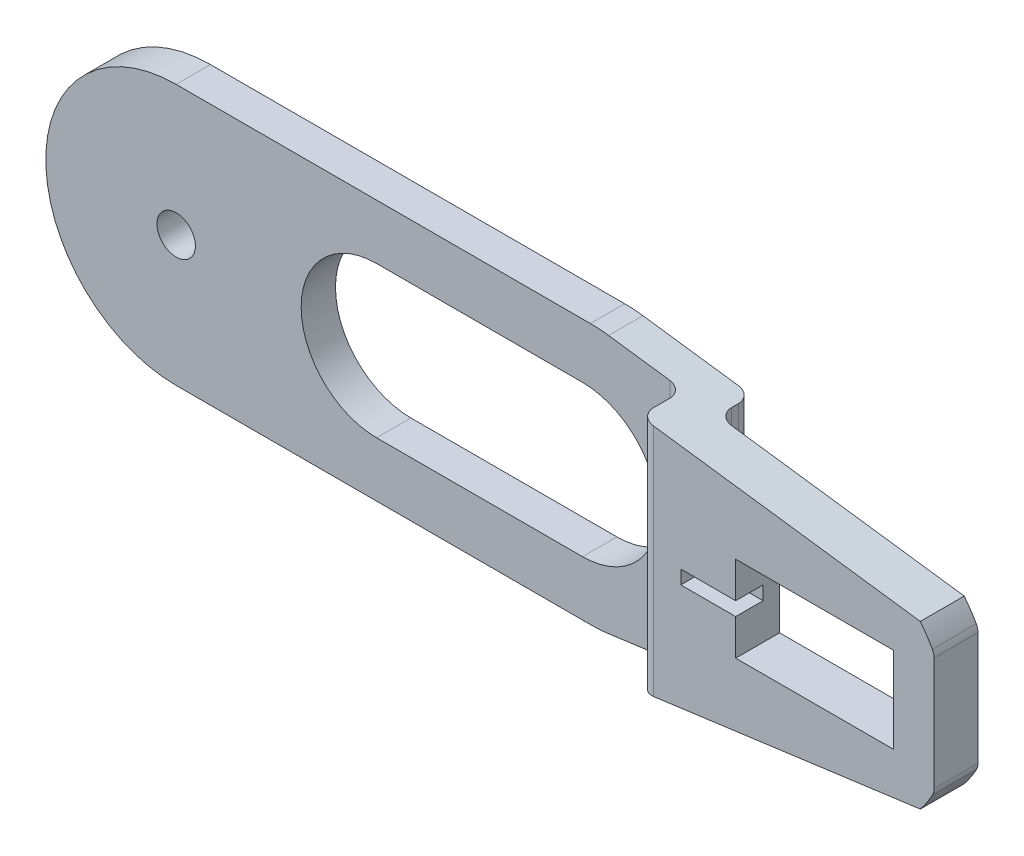
SolidWorks part; units mm, degrees
ref_plane "Front Plane" through (0, 0, 0) normal (0, 0, 1) x (1, 0, 0)
ref_plane "Top Plane" through (0, 0, 0) normal (0, 1, 0) x (1, 0, 0)
ref_plane "Right Plane" through (0, 0, 0) normal (1, 0, 0) x (0, 0, -1)
sketch "Sketch1" plane through (0, 0, 0) normal (0, 0, 1) x (1, 0, 0)
  line L0 (0, 0) -> (100, 0) construction
  line L1 (0, 19) -> (100, 19)
  line L2 (0, -19) -> (100, -19)
  line L3 (29.2177, 0) -> (59.2177, 0) construction
  line L4 (29.2177, 11) -> (59.2177, 11)
  line L5 (29.2177, -11) -> (59.2177, -11)
  line L7 (87.9426, -6.25) -> (117.9426, -6.25)
  line L8 (87.9426, -6.25) -> (87.9426, 6.25)
  line L9 (87.9426, 6.25) -> (117.9426, 6.25)
  line L11 (87.9426, -6.25) -> (125.1488, 13.036) construction
  line L12 (87.9426, 6.25) -> (124.7544, -12.8315) construction
  circle A0 centre (0, 0) radius 2.8
  arc A1 (0, 19) -> (0, -19) centre (0, 0) ccw
  arc A2 (100, -19) -> (117.9426, -6.25) centre (100, 0) ccw
  arc A3 (29.2177, 11) -> (29.2177, -11) centre (29.2177, 0) ccw
  arc A4 (59.2177, -11) -> (59.2177, 11) centre (59.2177, 0) ccw
  arc A5 (117.9426, 6.25) -> (100, 19) centre (100, 0) ccw
  point P8 (44.2177, 0)
  point P17 (100, 0)
  dimension "D1" = 38
  dimension "D2" = 5.6
  dimension "D4" = 38
  dimension "D3" = 100
  dimension "D5" = 30
  dimension "D6" = 8
  dimension "D7" = 12.5
  dimension "D8" = 30
extrude "Boss-Extrude1" add sketch "Sketch1" along normal blind 5
fillet "Fillet1" radius 2 2 edges at (117.9426, 6.25, 2.5) (117.9426, -6.25, 2.5)
sketch "Sketch2" plane through (0, 0, 5) normal (0, 0, 1) x (1, 0, 0)
  line L0 (73.9426, 19) -> (73.9426, -19)
  line L1 (100, 19) -> (0, 19) construction
  line L2 (0, -19) -> (100, -19) construction
  line L3 (87.9426, -6.25) -> (87.9426, 6.25) construction
  line L4 (100, 19) -> (73.9426, 19)
  line L6 (73.9426, -19) -> (100, -19)
  line L7 (114.864, -6.25) -> (87.9426, -6.25) construction
  line L8 (114.864, -6.25) -> (87.9426, -6.25)
  line L9 (87.9426, -6.25) -> (87.9426, 6.25)
  line L10 (87.9426, 6.25) -> (114.864, 6.25) construction
  line L11 (87.9426, 6.25) -> (114.864, 6.25)
  arc A0 (116.6127, 9.2206) -> (100, 19) centre (100, 0) ccw construction
  arc A1 (116.6127, 9.2206) -> (100, 19) centre (100, 0) ccw
  arc A2 (100, -19) -> (116.6127, -9.2206) centre (100, 0) ccw construction
  arc A3 (100, -19) -> (116.6127, -9.2206) centre (100, 0) ccw
  arc A4 (116.6127, -9.2206) -> (114.864, -6.25) centre (114.864, -8.25) ccw construction
  arc A5 (116.6127, -9.2206) -> (114.864, -6.25) centre (114.864, -8.25) ccw
  arc A6 (114.864, 6.25) -> (116.6127, 9.2206) centre (114.864, 8.25) ccw construction
  arc A7 (114.864, 6.25) -> (116.6127, 9.2206) centre (114.864, 8.25) ccw
  point P8 (87.9426, 0)
  dimension "D1" = 14
extrude "Boss-Extrude2" add sketch "Sketch2" along normal blind 6.4
fillet "Fillet2" radius 2 2 edges at (73.9426, 0, 11.4) (73.9426, 0, 5)
sketch "Sketch3" plane through (0, 0, 11.4) normal (0, 0, 1) x (1, 0, 0)
  line L0 (87.9426, 0) -> (75.9426, 0) construction
  line L1 (87.9426, -6.25) -> (87.9426, 6.25) construction
  line L2 (75.9426, 19) -> (75.9426, -19) construction
  line L3 (87.9426, 1) -> (79.9426, 1)
  line L4 (87.9426, -1) -> (79.9426, -1)
  line L5 (87.9426, 1) -> (87.9426, -1)
  line L6 (79.9426, 1) -> (79.9426, -1)
  line L8 (87.9426, 1) -> (75.9426, 1) construction
  line L9 (87.9426, -1) -> (75.9426, -1) construction
  dimension "D3" = 4
  dimension "D1" = 1
  dimension "D2" = 1
extrude "Cut-Extrude1" cut sketch "Sketch3" against normal blind 4
sketch "Sketch5" plane through (0, 0, 5) normal (0, 0, 1) x (1, 0, 0)
  line L0 (71.9426, 19) -> (0, 19) construction
  line L1 (71.9426, -19) -> (71.9426, 19) construction
  circle A0 centre (66.9426, 10) radius 2
  circle A1 centre (80.9146, -4.3103) radius 2
  dimension "D1" = 20
  dimension "D3" = 4
  dimension "D2" = 9
  dimension "D4" = 5
sketch "Sketch6" plane through (0, 0, 0) normal (0, 0, -1) x (-1, 0, 0)
  line L0 (-78.9426, -19) -> (-78.9426, 19)
  line L1 (0, -19) -> (-100, -19) construction
  line L2 (-100, 19) -> (0, 19) construction
  line L3 (-78.9426, -19) -> (-183.2299, -19)
  line L4 (-183.2299, -19) -> (-183.2299, 19)
  line L5 (-183.2299, 19) -> (-78.9426, 19)
  line L8 (-87.9426, -6.25) -> (-87.9426, 6.25) construction
  dimension "D1" = 9
extrude "Cut-Extrude3" cut sketch "Sketch6" against normal blind 5
fillet "Fillet3" radius 2 2 edges at (78.9426, 0, 5) (78.9426, 0, 0)
sketch "Sketch7" plane through (0, 0, 11.4) normal (0, 0, 1) x (1, 0, 0)
  line L0 (110.9426, 6.25) -> (110.9426, -6.25)
  line L1 (87.9426, 6.25) -> (114.864, 6.25) construction
  line L2 (114.864, -6.25) -> (87.9426, -6.25) construction
  line L3 (87.9426, 1) -> (87.9426, 6.25) construction
  line L4 (116.864, 8.25) -> (116.864, -8.25)
  line L5 (114.864, -6.25) -> (110.9426, -6.25)
  line L6 (110.9426, 6.25) -> (114.864, 6.25)
  arc A1 (114.864, 6.25) -> (116.6127, 9.2206) centre (114.864, 8.25) ccw construction
  arc A2 (114.864, 6.25) -> (116.6127, 9.2206) centre (114.864, 8.25) ccw
  arc A3 (116.6127, -9.2206) -> (114.864, -6.25) centre (114.864, -8.25) ccw construction
  arc A4 (116.864, -8.25) -> (114.864, -6.25) centre (114.864, -8.25) ccw
  line M7 (87.9426, 6.25) -> (114.864, 6.25)
  arc M8 (114.864, 6.25) -> (116.6127, 9.2206) centre (114.864, 8.25) ccw
  arc M14 (116.6127, -9.2206) -> (114.864, -6.25) centre (114.864, -8.25) ccw
  line M15 (114.864, -6.25) -> (87.9426, -6.25)
  dimension "D1" = 23
extrude "Boss-Extrude3" add sketch "Sketch7" against normal up to surface (6.4 mm away) contours L4 L0 M8 M7 M15 M14 up to face at (100.5087, 0, 5)
sketch "Sketch8" plane through (0, 0, 11.4) normal (0, 0, 1) x (1, 0, 0)
  line L0 (49.1665, 20.687) -> (202.8845, 0)
  line L1 (202.8845, 0) -> (49.1665, -20.687)
  line L2 (59.2177, 0) -> (157.474, 0) construction
  line L3 (49.1665, 20.687) -> (49.1665, 51.1557)
  line L4 (49.1665, -20.687) -> (49.1665, -34.8419)
  line L5 (49.1665, -34.8419) -> (221.7867, -38.9767)
  line L6 (221.7867, -38.9767) -> (223.8857, 48.653)
  line L7 (223.8857, 48.653) -> (49.1665, 52.8381)
  line L8 (49.1665, 52.8381) -> (49.1665, 51.1557)
extrude "Cut-Extrude4" cut sketch "Sketch8" against normal blind 52
fillet "Fillet4" radius 20 2 edges at (61.7017, -19, 2.5) (61.7017, 19, 2.5)
